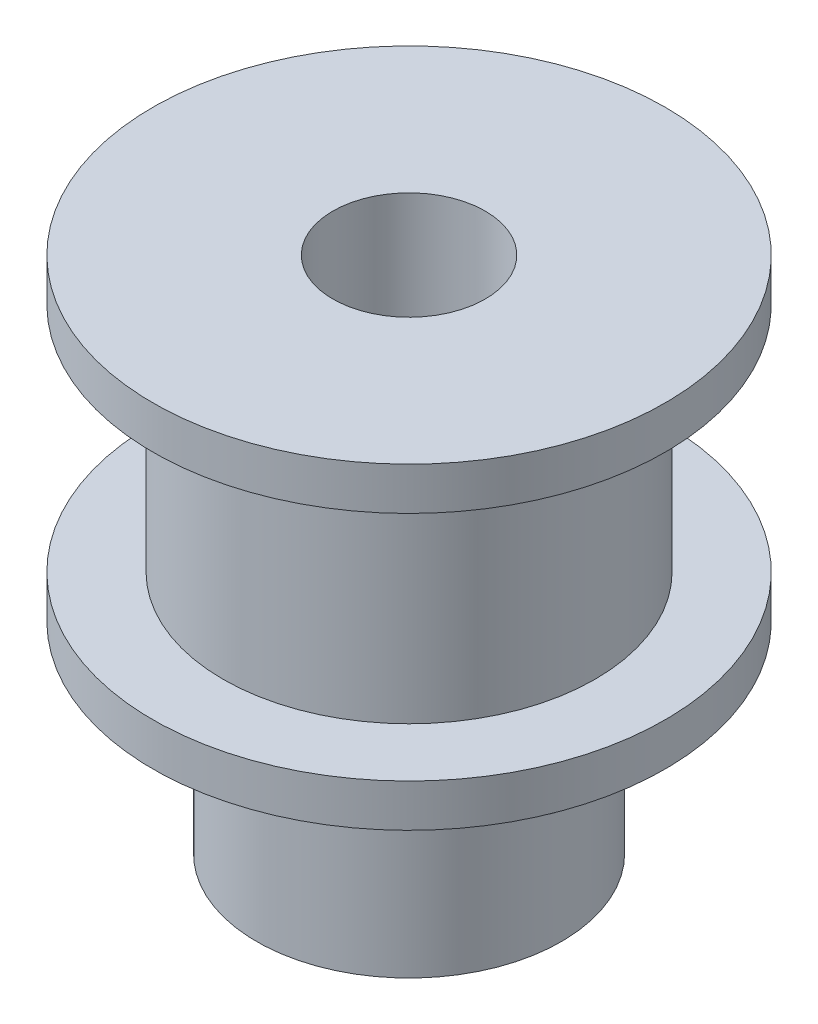
SolidWorks part; units mm, degrees
material "aluminio"
ref_plane "Alzado" through (0, 0, 0) normal (0, 0, 1) x (1, 0, 0)
ref_plane "Planta" through (0, 0, 0) normal (0, 1, 0) x (1, 0, 0)
ref_plane "Vista lateral" through (0, 0, 0) normal (1, 0, 0) x (0, 0, -1)
sketch "Croquis1" plane through (0, 0, 0) normal (0, 0, 1) x (1, 0, 0)
  line L0 (0, 0) -> (0, 36.7556) construction
  line L1 (8.4, 6.6) -> (5, 6.6)
  line L2 (5, 6.6) -> (5, 0)
  line L3 (2.5, 17) -> (8.4, 17)
  line L4 (8.4, 17) -> (8.4, 15.6)
  line L5 (8.4, 15.6) -> (6.1, 15.6)
  line L6 (6.1, 15.6) -> (6.1, 8)
  line L7 (6.1, 8) -> (8.4, 8)
  line L8 (8.4, 8) -> (8.4, 6.6)
  line L9 (5, 0) -> (2.5, 0)
  line L10 (2.5, 0) -> (2.5, 17)
  dimension "D1" = 1.4
  dimension "D2" = 1.4
  dimension "D3" = 17
  dimension "D4" = 5
  dimension "D5" = 12.2
  dimension "D6" = 16.8
  dimension "D7" = 16.8
  dimension "D8" = 10
  dimension "D9" = 10.4
revolve "Revolución1" add sketch "Croquis1" angle 360 about L0
sketch "Croquis2" plane through (0, 0, 0) normal (0, 0, 1) x (1, 0, 0)
  line L0 (-5, 0) -> (5, 0) construction
  circle A0 centre (0, 5) radius 1.25
  dimension "D1" = 5
  dimension "D2" = 2.5
extrude "Cortar-Extruir1" cut sketch "Croquis2" against normal up to next
cosmetic thread "Rosca cosmética2" parameters "D2"=3
pattern_circular "MatrizC1" count 2 over 90 about axis through (0, 0, 0) along (0, -1, 0) of "Cortar-Extruir1"
cosmetic thread "Rosca cosmética1" parameters "D2"=3
